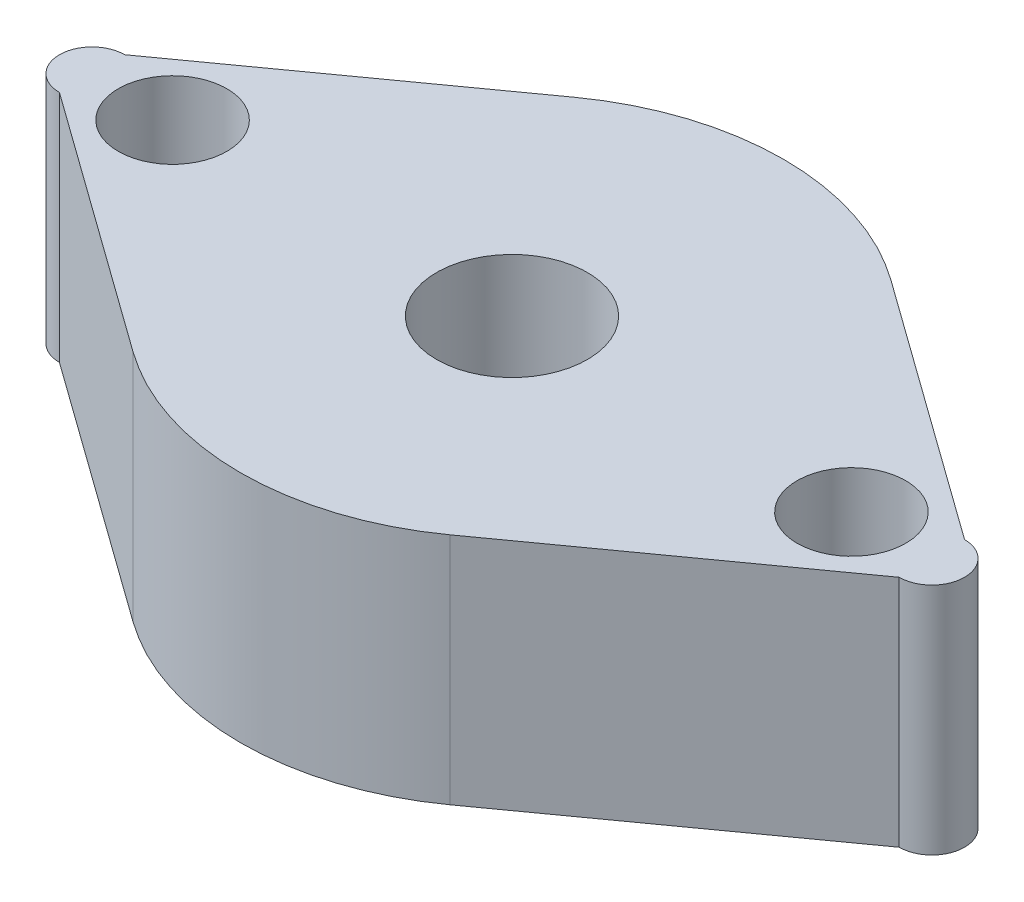
SolidWorks part; units mm, degrees
ref_plane "前视基准面" through (0, 0, 0) normal (0, 0, 1) x (1, 0, 0)
ref_plane "上视基准面" through (0, 0, 0) normal (0, 1, 0) x (1, 0, 0)
ref_plane "右视基准面" through (0, 0, 0) normal (1, 0, 0) x (0, 0, -1)
other "Configuration Table"
sketch "草图1" plane through (0, 0, 0) normal (0, 1, 0) x (1, 0, 0)
  line L0 (0, 0) -> (30, 0)
  line L1 (27.8352, 2.1648) -> (10.5031, 14.618)
  line L2 (27.8352, -2.1648) -> (10.5031, -14.618)
  line L3 (0, -1000) -> (0, 49000) construction
  line L4 (-27.8352, 2.1648) -> (-10.5031, 14.618)
  line L5 (-27.8352, -2.1648) -> (-10.5031, -14.618)
  circle A0 centre (0, 0) radius 18
  circle A1 centre (22.5, 0) radius 3.6
  circle A2 centre (27.8352, 0) radius 2.1648
  circle A3 centre (-27.8352, 0) radius 2.1648
  circle A4 centre (-22.5, 0) radius 3.6
  dimension "D1" = 36
  dimension "D3" = 7.2
  dimension "D2" = 30
  dimension "D4" = 7.5
extrude "凸台-拉伸1" add sketch "草图1" along normal blind 15.5 contours A0 L3 | L3 L0 A0 | L3 A0 L0 | A3 A4 L5 A0 L4 | A3 A4 | A2 L1 A0 L0 A1 | A2 A1 L0 A0 L2 | A2 L0 A1 | A2 A1 L0
sketch "草图2" plane through (0, 15.5, 0) normal (0, 1, 0) x (1, 0, 0)
  circle A0 centre (0, 0) radius 5
  dimension "D1" = 10
extrude "切除-拉伸1" cut sketch "草图2" against normal blind 31.5
